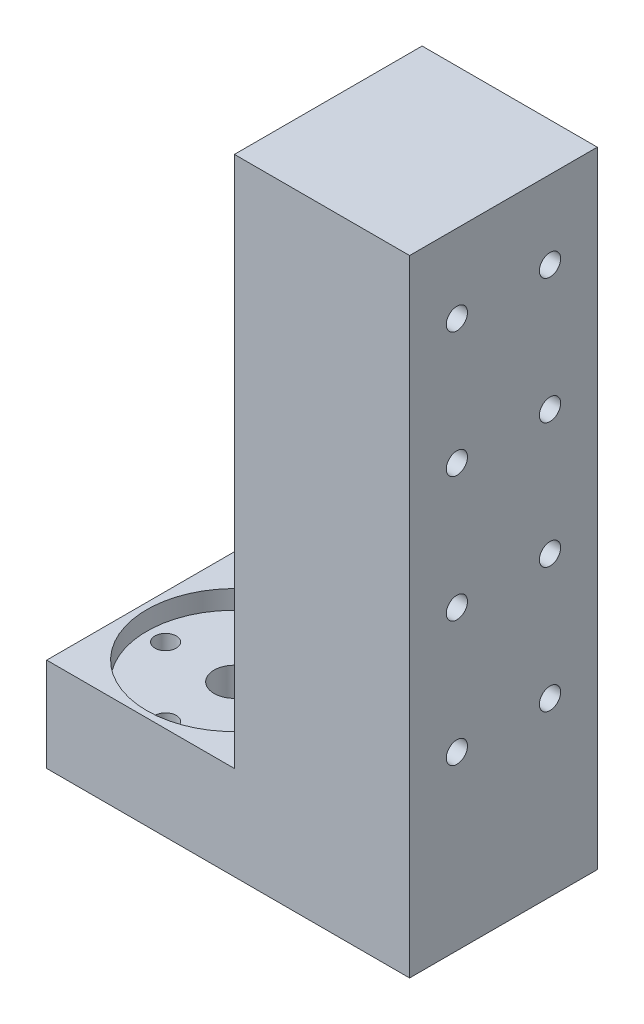
SolidWorks part; units mm, degrees
ref_plane "Front Plane" through (0, 0, 0) normal (0, 0, 1) x (1, 0, 0)
ref_plane "Top Plane" through (0, 0, 0) normal (0, 1, 0) x (1, 0, 0)
ref_plane "Right Plane" through (0, 0, 0) normal (1, 0, 0) x (0, 0, -1)
sketch "Sketch2" plane through (0, 0, 0) normal (0, 0, 1) x (1, 0, 0)
  line L0 (0, 0) -> (0, 15)
  line L1 (0, 15) -> (30, 15)
  line L3 (30, 0) -> (0, 0)
  line L4 (30, 0) -> (58, 0)
  line L5 (58, 0) -> (58, 100)
  line L6 (58, 100) -> (30, 100)
  line L7 (30, 100) -> (30, 15)
  dimension "D1" = 30
  dimension "D2" = 15
  dimension "D3" = 28
  dimension "D4" = 100
extrude "Boss-Extrude1" add sketch "Sketch2" along normal blind 30
sketch "Sketch3" plane through (0, 15, 0) normal (0, 1, 0) x (1, 0, 0)
  circle A0 centre (15, -15) radius 14
  dimension "D1" = 28
extrude "Cut-Extrude1" cut sketch "Sketch3" against normal blind 3
sketch "Sketch4" plane through (0, 12, 0) normal (0, 1, 0) x (1, 0, 0)
  circle A1 centre (15, -4) radius 1.7
  circle A2 centre (26, -15) radius 1.7
  circle A3 centre (15, -26) radius 1.7
  circle A4 centre (4, -15) radius 1.7
  circle A5 centre (15, -15) radius 3.25
  dimension "D1" = 22
  dimension "D2" = 6.5
  dimension "D3" = 3.4
extrude "Cut-Extrude2" cut sketch "Sketch4" against normal through all
sketch "Sketch5" plane through (30, 0, 0) normal (-1, 0, 0) x (0, 0, 1)
  line L0 (15, 15) -> (15, 100) construction
  line L1 (30, 15) -> (0, 15) construction
  line L2 (30, 100) -> (0, 100) construction
  circle A0 centre (7.5589, 27.5) radius 1.7
  circle A1 centre (7.5589, 47.5) radius 1.7
  circle A2 centre (7.5589, 67.5) radius 1.7
  circle A3 centre (7.5589, 87.5) radius 1.7
  circle A4 centre (22.4411, 27.5) radius 1.7
  circle A5 centre (22.4411, 47.5) radius 1.7
  circle A6 centre (22.4411, 67.5) radius 1.7
  circle A7 centre (22.4411, 87.5) radius 1.7
  point P14 (0, 0)
  point P15 (0, 0)
  dimension "D2" = 3.4
  dimension "D1" = 85
  dimension "D3" = 12.5
  dimension "D4" = 12.5
  dimension "D5" = 20
  dimension "D6" = 20
  dimension "D7" = 20
extrude "Cut-Extrude3" cut sketch "Sketch5" against normal through all
equation "\"M3_Diameter\"= 3.4mm"
